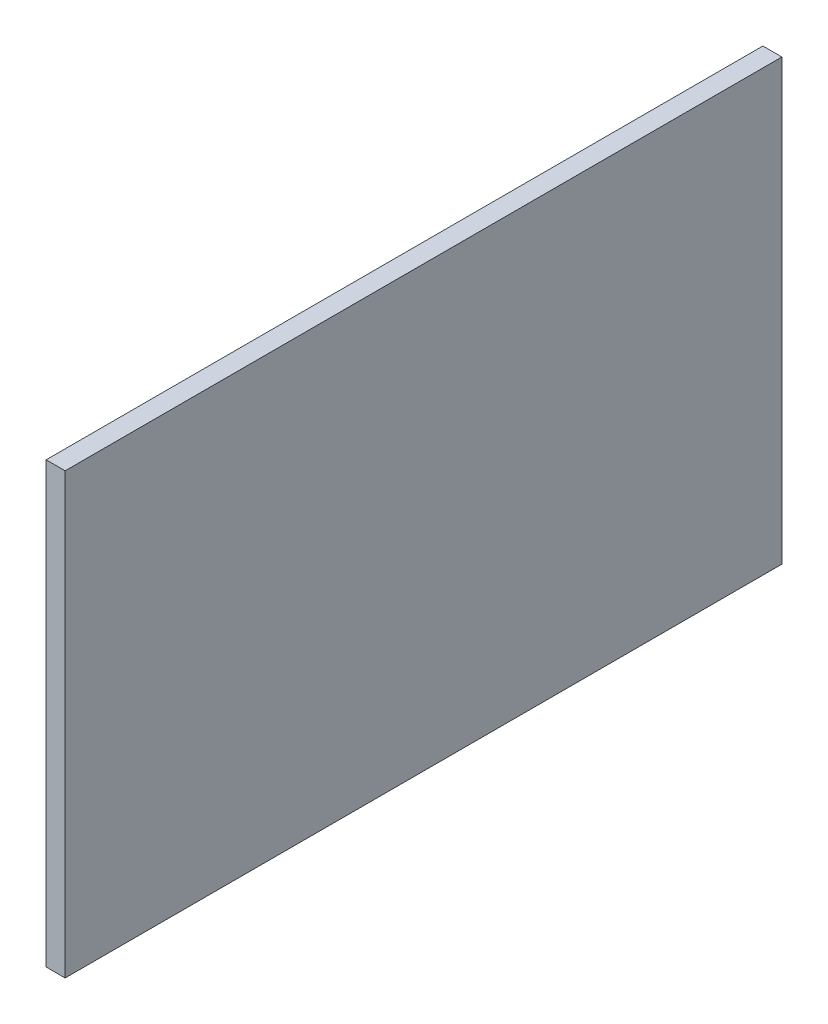
SolidWorks part; units mm, degrees
ref_plane "Front Plane" through (0, 0, 0) normal (0, 0, 1) x (1, 0, 0)
ref_plane "Top Plane" through (0, 0, 0) normal (0, 1, 0) x (1, 0, 0)
ref_plane "Right Plane" through (0, 0, 0) normal (1, 0, 0) x (0, 0, -1)
sketch "Sketch1" plane through (0, 0, 0) normal (1, 0, 0) x (0, 0, -1)
  line L1 (0, 0) -> (452, 0)
  line L2 (0, 0) -> (0, 277)
  line L3 (0, 277) -> (452, 277)
  line L4 (452, 0) -> (452, 277)
  dimension "D1" = 277
  dimension "D2" = 452
extrude "Boss-Extrude1" add sketch "Sketch1" along normal blind 12
